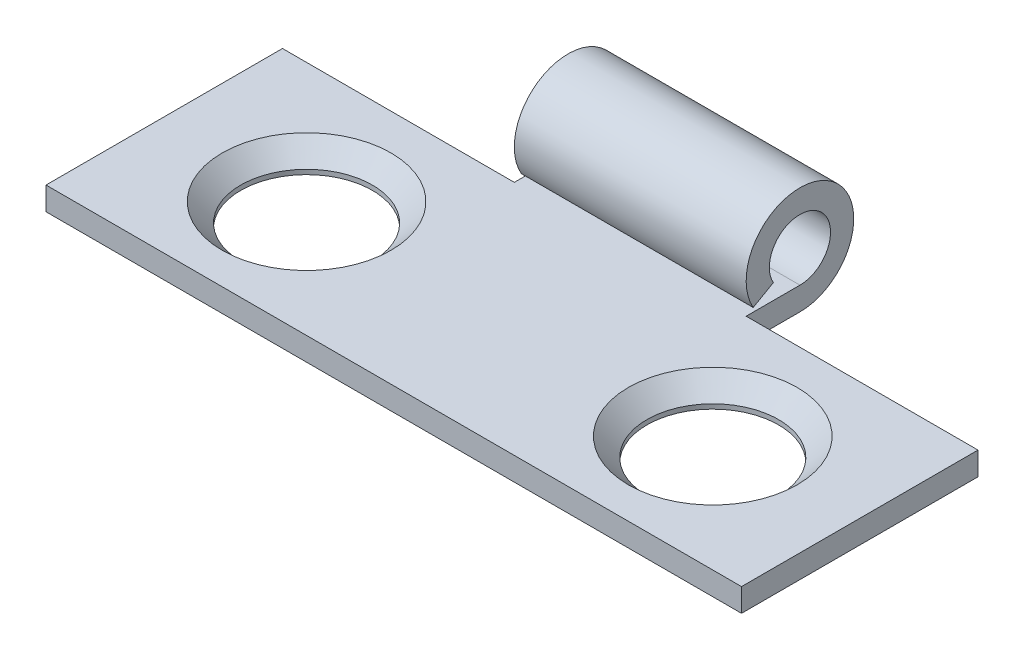
SolidWorks part; units mm, degrees
ref_plane "Front Plane" through (0, 0, 0) normal (0, 0, 1) x (1, 0, 0)
ref_plane "Top Plane" through (0, 0, 0) normal (0, 1, 0) x (1, 0, 0)
ref_plane "Right Plane" through (0, 0, 0) normal (1, 0, 0) x (0, 0, -1)
sketch "Sketch1" plane through (0, 0, 0) normal (0, 1, 0) x (1, 0, 0)
  line L0 (-9.525, 0) -> (9.525, 0) construction
  line L1 (-9.525, -7.9502) -> (-9.525, 7.9502) construction
  line L2 (-9.525, -7.9502) -> (-5.5626, -7.9502) construction
  line L3 (5.5626, -4.7752) -> (-5.5626, -4.7752) construction
  line L4 (-5.5626, -7.9502) -> (5.5626, -7.9502) construction
  line L5 (9.525, -7.9502) -> (9.525, -4.7752) construction
  line L6 (5.5626, -7.9502) -> (9.525, -7.9502) construction
  line L7 (-9.525, 7.9502) -> (-4.7498, 7.9502) construction
  line L8 (-4.7498, 7.9502) -> (11.1252, 7.9502) construction
  line L9 (11.1252, 7.9502) -> (27.0002, 7.9502) construction
  line L10 (27.0002, 7.9502) -> (30.9626, 7.9502) construction
  line L11 (5.5626, -7.0866) -> (5.5626, -2.4638) construction
  line L12 (5.5626, -4.7752) -> (9.525, -4.7752) construction
  line L13 (-5.5626, -4.7752) -> (-5.5626, -7.9502) construction
  line L14 (5.5626, 4.7752) -> (-5.5626, 4.7752) construction
  point P3 (5.5626, -6.5786)
  point P4 (0, 0)
  point P8 (-9.525, 0)
  point P17 (-3.175, 0)
  point P21 (5.5626, -4.7752)
  dimension "Frame Leaf Height" = 19.05
  dimension "Overall Width" = 15.9004
  dimension "Hole to End 1" = 3.9624
  dimension "Hole to End 2" = 3.9624
  dimension "D1" = 3.9624
  dimension "D2" = 4.7752
  dimension "D4" = 15.875
  dimension "D6" = 15.875
  dimension "Knuckle Length" = 6.35
  dimension "Hole Chamfer Dia" = 4.6228
  dimension "Hole Center to Pin" = 4.7752
  dimension "Door Leaf Height" = 19.05
  dimension "Mounting Hole Diameter" = 3.6068
  dimension "D3" = 11.1252
  dimension "Frame Leaf Width" = 7.9502
  dimension "Door Leaf Width" = 7.9502
sketch "Sketch2" plane through (0, 0, 0) normal (1, 0, 0) x (0, 0, -1)
  line L2 (0, -1.4732) -> (0, -0.8382) construction
  line L4 (0, 0.8382) -> (0, -0.8382) construction
  point P8 (0, 0)
  dimension "Leaf Thickness" = 0.635
  dimension "Pin Diameter" = 1.6764
sketch "Sketch3" plane through (0, 0, 0) normal (1, 0, 0) x (0, 0, -1)
  line L3 (0, 0) -> (-1.4732, -0.8382) construction
  line L4 (0, -1.4732) -> (-7.9502, -1.4732)
  line L5 (-7.9502, -1.4732) -> (-7.9502, -0.8382)
  line L7 (-7.9502, -0.8382) -> (0, -0.8382)
  line L8 (-7.9502, 0) -> (7.9502, 0) construction
  line L9 (-0.7285, -0.4145) -> (-1.2805, -0.7285)
  line L11 (-1.4732, 0) -> (-1.4732, -0.8382) construction
  circle A4 centre (0, 0) radius 0.8382 construction
  circle A5 centre (0, 0) radius 1.4732 construction
  arc A8 (-0.7285, -0.4145) -> (0, -0.8382) centre (0, 0) cw
  arc A9 (-1.2805, -0.7285) -> (0, -1.4732) centre (0, 0) cw
  point P0 (-1.2805, -0.7285)
  point P13 (-0.7285, -0.4145)
extrude "Boss-Extrude1" add sketch "Sketch3" along normal mid plane 19.05
pattern_circular "CirPattern1" [suppressed] count 2 over 360 about axis through (0, 0.8382, 0) along (0, -1, 0)
sketch "Sketch4" plane through (0, 0, 0) normal (0, 1, 0) x (1, 0, 0)
  line L0 (-9.525, -1.4732) -> (9.525, -1.4732) construction
  line L1 (-9.525, -1.4732) -> (9.525, -1.4732) construction
  line L2 (9.525, 1.4732) -> (-9.525, 1.4732) construction
  line L3 (9.525, 1.4732) -> (-9.525, 1.4732) construction
  line L4 (-3.175, -1.4732) -> (-3.175, 1.4732)
  line L6 (-3.175, 1.4732) -> (3.175, 1.4732)
  line L7 (3.175, -1.4732) -> (-3.175, -1.4732)
  line L8 (3.175, 1.4732) -> (3.175, -1.4732)
  line L9 (-9.525, 1.4732) -> (-3.175, 1.4732)
  line L10 (-9.525, 1.4732) -> (-9.525, -1.4732)
  line L11 (-9.525, -1.4732) -> (-3.175, -1.4732)
  line L12 (-3.175, 1.4732) -> (-3.175, -1.4732)
  line L13 (3.175, 1.4732) -> (9.525, 1.4732)
  line L14 (3.175, 1.4732) -> (3.175, -1.4732)
  line L15 (3.175, -1.4732) -> (9.525, -1.4732)
  line L16 (9.525, 1.4732) -> (9.525, -1.4732)
  point P8 (-3.175, 0)
  dimension "D1" = 6.35
extrude "Cut-Extrude1" cut sketch "Sketch4" against normal through all both and the other way through all contours L10 L11 L4 L9 | L16 L13 L8 L15
sketch "Sketch10" [suppressed] plane through (0, 0, 0) normal (0, 1, 0) x (1, 0, 0)
  line L0 (9.525, 1.4732) -> (-9.525, 1.4732) construction
  line L5 (-3.1623, 1.4732) -> (-9.525, 1.4732)
  line L6 (-3.1623, 1.4732) -> (-3.1623, -1.4732)
  line L7 (-3.1623, -1.4732) -> (-9.525, -1.4732)
  line L8 (-9.525, 1.4732) -> (-9.525, -1.4732)
  line L9 (3.1623, 1.4732) -> (9.525, 1.4732)
  line L10 (3.1623, 1.4732) -> (3.1623, -1.4732)
  line L11 (3.1623, -1.4732) -> (9.525, -1.4732)
  line L12 (9.525, 1.4732) -> (9.525, -1.4732)
  dimension "D1" = 0.0127
extrude "Cut-Extrude4" [suppressed] cut sketch "Sketch10" against normal through all both and the other way through all
sketch "Sketch5" plane through (0, -0.8382, 0) normal (0, 1, 0) x (1, 0, 0)
  line L0 (5.5626, -4.7752) -> (-5.5626, -4.7752) construction
  line L1 (0, -4.7752) -> (0, -7.9502) construction
  line L2 (-5.5626, -4.7752) -> (-5.5626, -7.9502) construction
  line L3 (9.525, -7.9502) -> (-9.525, -7.9502) construction
  circle A0 centre (5.5626, -4.7752) radius 2.3114
  circle A2 centre (-5.5626, -4.7752) radius 2.3114
extrude "Cut-Extrude2" cut sketch "Sketch5" against normal through all draft 45
sketch "Sketch9" plane through (0, 0, 0) normal (0, 1, 0) x (1, 0, 0)
  circle A0 centre (5.5626, -4.7752) radius 1.8034
  circle A2 centre (-5.5626, -4.7752) radius 1.8034
  dimension "D1" = 3.6068
extrude "Cut-Extrude3" cut sketch "Sketch9" against normal through all both and the other way through all
sketch "Sketch11" [suppressed] plane through (0, -0.8382, 0) normal (0, 1, 0) x (1, 0, 0)
  circle A0 centre (5.5626, 4.7752) radius 2.3114
  circle A1 centre (-5.5626, 4.7752) radius 2.3114
  circle A2 centre (-5.5626, -4.7752) radius 2.3114 construction
sketch "Sketch6" plane through (0, 0, 0) normal (1, 0, 0) x (0, 0, -1)
  circle A0 centre (0, 0) radius 0.8382
  dimension "D1" = 1.6764
sketch "Sketch7" [suppressed] plane through (0, 0, 0) normal (1, 0, 0) x (0, 0, -1)
  line L0 (-0.8382, 0) -> (0.8382, 0) construction
  line L1 (-7.9502, 0) -> (7.9502, 0) construction
  line L2 (7.9502, -0.8382) -> (7.9502, -1.4732) construction
  line L3 (7.9502, -0.8382) -> (7.9502, -1.4732) construction
  line L4 (7.9502, -1.4732) -> (-7.9502, -1.4732) construction
  line L5 (-7.9502, -1.4732) -> (-7.9502, -0.8382)
  point P6 (0, 0)
  point P8 (0.8382, 0)
  point P9 (-0.8382, 0)
  point P12 (7.9502, -0.8382)
  point P13 (7.9502, -1.4732)
  point P14 (-7.9502, -1.4732)
  dimension "D1" = 1.6764
  dimension "D2" = 15.9004
  dimension "D3" = 0.635
sketch "Sketch8" [suppressed] plane through (0, 0, 0) normal (0, 1, 0) x (1, 0, 0)
  line L0 (-7.874, -4.7752) -> (-3.2512, -4.7752) construction
  line L1 (5.5626, 4.7752) -> (-5.5626, 4.7752) construction
  line L2 (3.2512, -4.7752) -> (7.874, -4.7752) construction
  line L3 (-5.5626, -2.4638) -> (-5.5626, -7.0866) construction
  line L5 (5.5626, -2.4638) -> (5.5626, -7.0866) construction
  line L6 (-5.5626, 7.0866) -> (-5.5626, 2.4638) construction
  line L7 (-7.874, 4.7752) -> (-3.2512, 4.7752) construction
  line L10 (5.5626, 7.0866) -> (5.5626, 2.4638) construction
  line L11 (3.2512, 4.7752) -> (7.874, 4.7752) construction
  line L12 (5.5626, 4.7752) -> (7.197, 6.4096) construction
  circle A1 centre (-5.5626, -4.7752) radius 2.3114 construction
  circle A3 centre (5.5626, -4.7752) radius 2.3114 construction
  circle A7 centre (5.5626, 4.7752) radius 2.3114 construction
  circle A8 centre (-5.5626, 4.7752) radius 2.3114 construction
  circle A9 centre (5.5626, 4.7752) radius 2.3114 construction
  point P2 (-9.525, 0)
  point P7 (-5.5626, -4.7752)
  point P19 (5.5626, -4.7752)
  point P25 (-9.525, 7.9502)
  point P26 (30.9626, 7.9502)
  point P28 (-9.525, -7.9502)
  point P30 (9.525, -7.9502)
  point P32 (-7.874, -4.7752)
  point P33 (-5.5626, -2.4638)
  point P34 (-3.2512, -4.7752)
  point P35 (-5.5626, -7.0866)
  point P40 (7.874, -4.7752)
  point P41 (5.5626, -7.0866)
  point P42 (3.2512, -4.7752)
  point P43 (5.5626, -2.4638)
  point P67 (5.5626, -7.9502)
  point P69 (-5.5626, -7.9502)
  point P71 (-4.7498, 7.9502)
  point P73 (-5.5626, 4.7752)
  point P76 (5.5626, 4.7752)
  point P77 (27.0002, 7.9502)
  point P78 (11.1252, 7.9502)
  point P82 (-5.5626, 7.0866)
  point P83 (-7.874, 4.7752)
  point P84 (-5.5626, 2.4638)
  point P85 (-3.2512, 4.7752)
  point P90 (5.5626, 2.4638)
  point P91 (3.2512, 4.7752)
  point P92 (5.5626, 7.0866)
  point P97 (7.197, 6.4096)
  dimension "D1" = 45
equation "\"D1@Sketch1\"=\"Hole to End 1@Sketch1\""
equation "\"D6@Sketch1\"=\"D4@Sketch1\""
equation "\"D1@Boss-Extrude1\" = \"Frame Leaf Height@Sketch1\""
equation "\"D1@Sketch4\"=\"Knuckle Length@Sketch1\""
equation "\"D1@Sketch6\"=\"Pin Diameter@Sketch2\""
equation "\"D1\" = \"Frame Leaf Height@Sketch1\""
equation "\"D1@Sketch7\"=\"Pin Diameter@Sketch2\""
equation "\"D2@Sketch7\"=\"Overall Width@Sketch1\""
equation "\"D3@Sketch7\"=\"Leaf Thickness@Sketch2\""
equation "\"Knuckle Length@Sketch1\"=\"Frame Leaf Height@Sketch1\" / 3"
equation "\"Hole to End 2@Sketch1\"=\"Hole to End 1@Sketch1\""
equation "\"Hole Chamfer Dia@Sketch1\"=\"Mounting Hole Diameter@Sketch1\"+.04"
